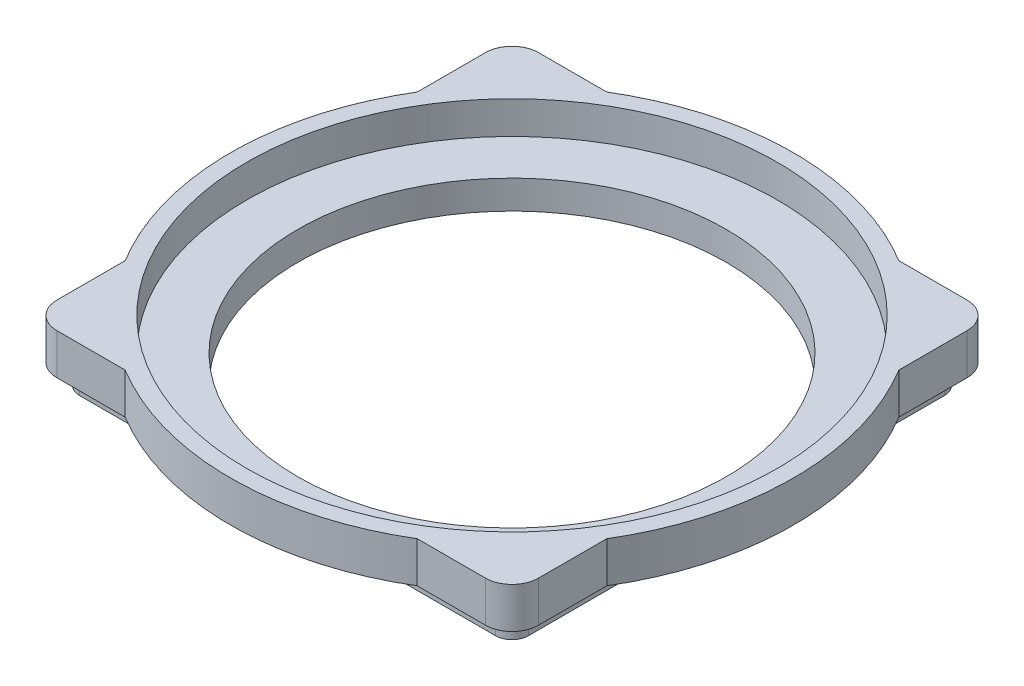
SolidWorks part; units mm, degrees
material "ABS"
ref_plane "Front" through (0, 0, 0) normal (0, 0, 1) x (1, 0, 0)
ref_plane "Top" through (0, 0, 0) normal (0, 1, 0) x (1, 0, 0)
ref_plane "Right" through (0, 0, 0) normal (1, 0, 0) x (0, 0, -1)
sketch "Sketch1" plane through (0, 0, 0) normal (0, 1, 0) x (1, 0, 0)
  line L1 (59, 59) -> (-59, 59)
  line L2 (59, 59) -> (59, -59)
  line L3 (59, -59) -> (-59, -59)
  line L4 (-59, 59) -> (-59, -59)
  line L5 (59, 59) -> (-59, -59) construction
  line L6 (59, -59) -> (-59, 59) construction
  point P0 (0, 0)
  dimension "D1" = 118
extrude "Boss-Extrude1" add sketch "Sketch1" along normal blind 15
sketch "Sketch2" plane through (0, 0, 0) normal (0, -1, 0) x (1, 0, 0)
  line L1 (-55, -55) -> (55, -55)
  line L2 (-55, -55) -> (-55, 55)
  line L3 (-55, 55) -> (55, 55)
  line L4 (55, -55) -> (55, 55)
  line L5 (-55, -55) -> (55, 55) construction
  line L6 (-55, 55) -> (55, -55) construction
  line L10 (-59, 59) -> (-59, -59)
  line L11 (-59, -59) -> (59, -59)
  line L12 (59, -59) -> (59, 59)
  line L13 (59, 59) -> (-59, 59)
  line L14 (-59, 59) -> (-59, -59)
  line L15 (-59, -59) -> (59, -59)
  line L16 (59, -59) -> (59, 59)
  line L17 (59, 59) -> (-59, 59)
  point P0 (0, 0)
  dimension "D2" = 110
  dimension "D1" = 0
extrude "Cut-Extrude1" cut sketch "Sketch2" against normal blind 5
sketch "Sketch6" plane through (0, 15, 0) normal (0, 1, 0) x (1, 0, 0)
  circle A0 centre (0, 0) radius 69
  dimension "D1" = 138
extrude "Boss-Extrude2" add sketch "Sketch6" against normal up to surface (10 mm away) up to face at (0, 5, 0)
sketch "Sketch3" plane through (0, 15, 0) normal (0, 1, 0) x (1, 0, 0)
  circle A0 centre (0, 0) radius 52.5
  dimension "D1" = 105
extrude "Cut-Extrude2" cut sketch "Sketch3" against normal through all
sketch "Sketch4" plane through (0, 15, 0) normal (0, 1, 0) x (1, 0, 0)
  circle A0 centre (0, 0) radius 65
  dimension "D1" = 130
extrude "Cut-Extrude3" cut sketch "Sketch4" against normal blind 8 contours A0
fillet "Fillet1" radius 4 4 edges at (-55, 2.5, -55) (55, 2.5, -55) (55, 2.5, 55) (-55, 2.5, 55)
fillet "Fillet2" radius 6.5 4 edges at (-59, 10, 59) (-59, 10, -59) (59, 10, 59) (59, 10, -59)
